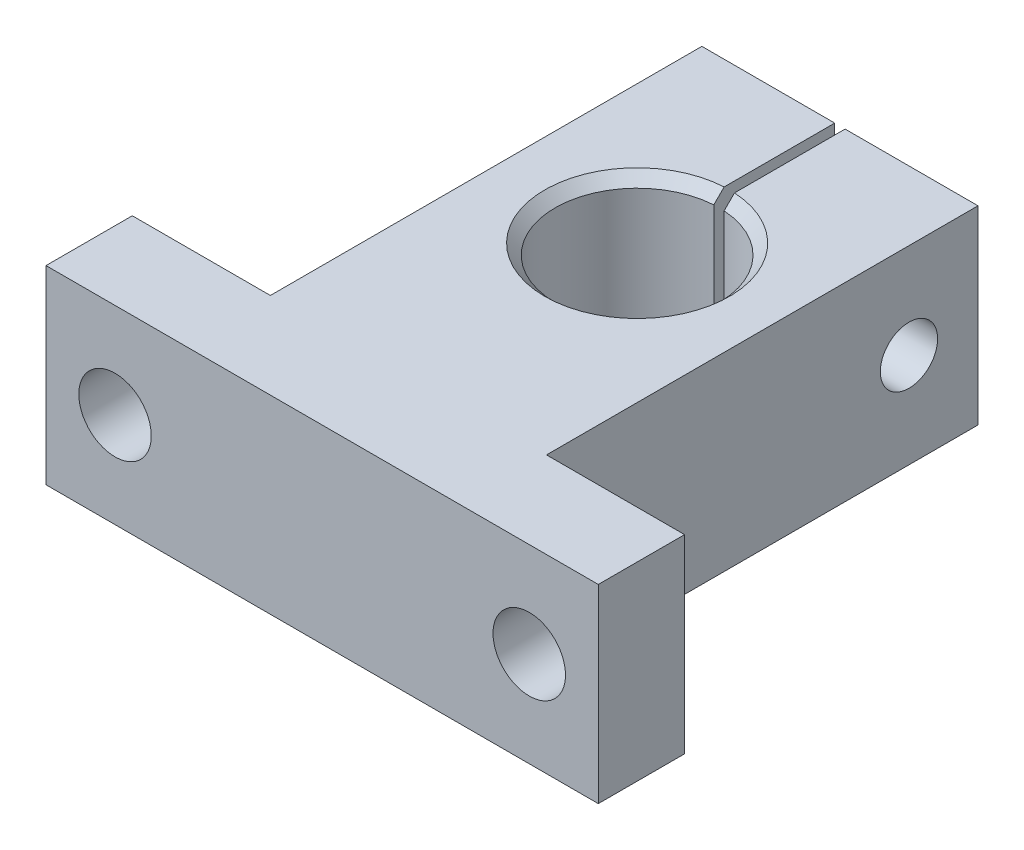
SolidWorks part; units mm, degrees
material "6061 Alloy"
ref_plane "Front Plane" through (0, 0, 0) normal (0, 0, 1) x (1, 0, 0)
ref_plane "Top Plane" through (0, 0, 0) normal (0, 1, 0) x (1, 0, 0)
ref_plane "Right Plane" through (0, 0, 0) normal (1, 0, 0) x (0, 0, -1)
sketch "Sketch1" plane through (0, 0, 0) normal (0, 1, 0) x (1, 0, 0)
  line L0 (0, 6.0325) -> (0, 14.9225) construction
  line L1 (10.16, 14.9225) -> (0.381, 14.9225)
  line L2 (-10.16, 14.9225) -> (-10.16, -16.8275)
  line L3 (10.16, 14.9225) -> (10.16, -16.8275)
  line L4 (10.16, -16.8275) -> (20.32, -16.8275)
  line L5 (20.32, -16.8275) -> (20.32, -23.1775)
  line L6 (20.32, -23.1775) -> (-20.32, -23.1775)
  line L7 (-20.32, -23.1775) -> (-20.32, -16.8275)
  line L8 (-20.32, -16.8275) -> (-10.16, -16.8275)
  line L9 (0.381, 6.0205) -> (0.381, 14.9225)
  line L10 (-0.381, 6.0205) -> (-0.381, 14.9225)
  line L13 (-0.381, 14.9225) -> (-10.16, 14.9225)
  line L14 (-0.381, 6.0325) -> (-0.381, 14.9225) construction
  line L15 (0.381, 6.0325) -> (0.381, 14.9225) construction
  arc A0 (-0.381, 6.0205) -> (0.381, 6.0205) centre (0, 0) ccw
  point P8 (0, 14.9225)
  dimension "D1" = 12.065
  dimension "D2" = 8.89
  dimension "D3" = 20.32
  dimension "D4" = 0.381
  dimension "D5" = 0.381
extrude "Boss-Extrude1" add sketch "Sketch1" along normal blind 13.97
sketch "Sketch2" plane through (0, 0, 16.8275) normal (0, 0, -1) x (-1, 0, 0)
  line L0 (0, 0) -> (0, 13.97) construction
  line L1 (6.0325, 13.97) -> (-6.0325, 13.97) construction
  line L2 (15.24, 6.985) -> (-15.24, 6.985) construction
  circle A0 centre (-15.24, 6.985) radius 2.667
  circle A1 centre (15.24, 6.985) radius 2.667
  point P8 (0, 6.985)
  dimension "D1" = 5.334
  dimension "D2" = 5.334
  dimension "D3" = 30.48
extrude "Cut-Extrude1" cut sketch "Sketch2" against normal blind 13.97
sketch "Sketch3" plane through (-10.16, 0, 0) normal (-1, 0, 0) x (0, 0, 1)
  line L0 (-14.9225, 13.97) -> (-14.9225, 0) construction
  line L1 (-14.9225, 6.985) -> (-9.8425, 6.985) construction
  circle A0 centre (-9.8425, 6.985) radius 3.81
  dimension "D2" = 7.62
  dimension "D1" = 5.08
extrude "Cut-Extrude2" cut sketch "Sketch3" against normal blind 4.826
sketch "Sketch4" plane through (-5.334, 0, 0) normal (-1, 0, 0) x (0, 0, 1)
  circle A0 centre (-9.8425, 6.985) radius 2.1082
  dimension "D1" = 4.2164
extrude "Cut-Extrude3" cut sketch "Sketch4" against normal blind 17.272
chamfer "Chamfer1" distance 0.762 angle 45 5 edges at (-10.16, 6.985, -6.0325) (12.573, 6.985, 16.8275) (-17.907, 6.985, 16.8275) (0, 0, 6.0325) (0, 13.97, 6.0325)
